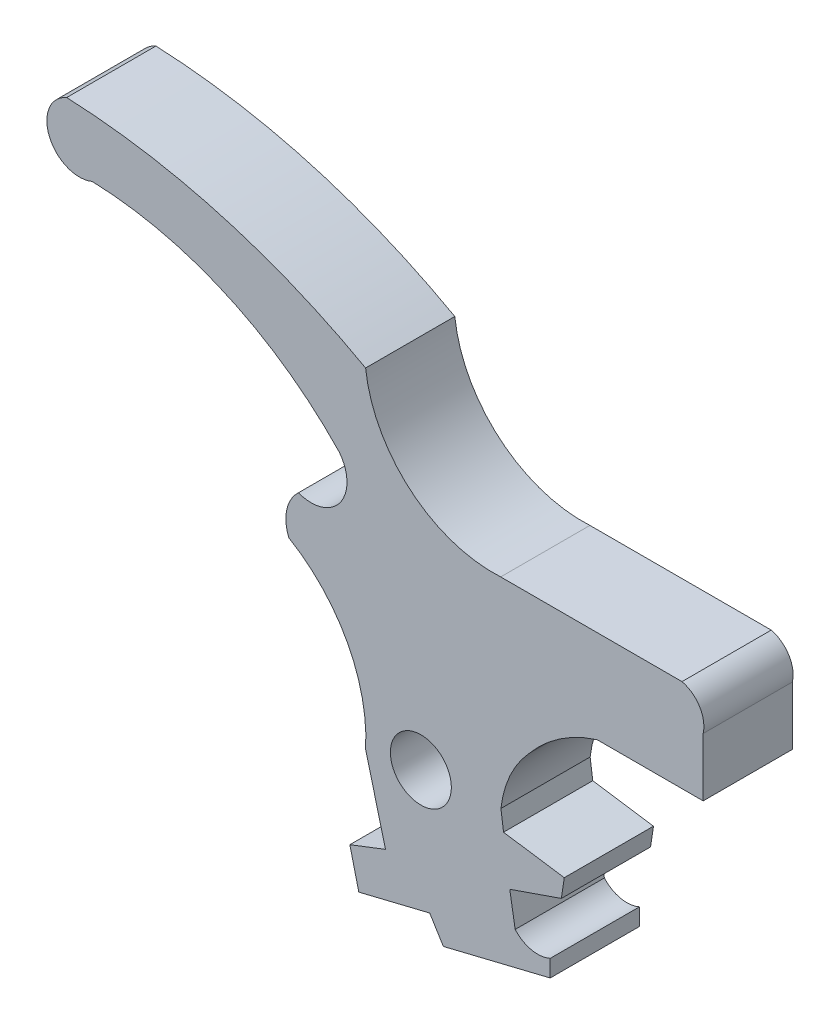
SolidWorks part; units mm, degrees
ref_plane "정면" through (0, 0, 0) normal (0, 0, 1) x (1, 0, 0)
ref_plane "윗면" through (0, 0, 0) normal (0, 1, 0) x (1, 0, 0)
ref_plane "우측면" through (0, 0, 0) normal (1, 0, 0) x (0, 0, -1)
sketch "스케치1" plane through (0, 0, 0) normal (0, 0, 1) x (1, 0, 0)
  line L0 (-3.7145, -0.6598) -> (-2.3786, -5.8179)
  line L1 (5.5588, -0.8516) -> (9.6431, -1.4566)
  line L2 (5.3688, 13.9228) -> (17.5625, 13.9228)
  line L3 (18.9842, 11.6084) -> (18.9842, 7.685)
  line L4 (18.9842, 7.685) -> (11.8569, 7.685)
  line L5 (5.3846, 0.445) -> (5.5588, -0.8516)
  line L7 (8.6994, -6.6263) -> (8.6994, -7.7709)
  line L8 (8.6994, -7.7709) -> (1.5135, -9.5269)
  line L9 (1.5135, -9.5269) -> (0.5954, -8.0402)
  line L10 (0.5954, -8.0402) -> (-4.1735, -9.2056)
  line L11 (-4.1735, -9.2056) -> (-4.775, -6.7438)
  line L12 (-4.775, -6.7438) -> (-2.3786, -5.8179)
  line L13 (9.6431, -1.4566) -> (9.4484, -2.7628)
  line L14 (9.4484, -2.7628) -> (5.9768, -3.9634)
  line L15 (5.9768, -3.9634) -> (6.3425, -6.1211)
  circle A0 centre (0, 0) radius 2.05
  arc A1 (-8.8751, 9.0777) -> (-3.7145, -0.6598) centre (-14.3053, -0.0364) cw
  arc A2 (-8.8751, 9.0777) -> (-8.2327, 12.0241) centre (-6.4445, 10.091) cw
  arc A3 (-8.2327, 12.0241) -> (-5.4873, 15.7643) centre (-7.3745, 14.2718) ccw
  arc A4 (-5.4873, 15.7643) -> (-22.1053, 23.2184) centre (-22.8782, -0.7557) ccw
  arc A5 (-22.1053, 23.2184) -> (-23.8173, 27.25) centre (-22.9613, 25.2342) cw
  arc A6 (-23.8173, 27.25) -> (-3.7176, 21.5479) centre (-25.8237, -18.099) cw
  arc A7 (-3.7176, 21.5479) -> (5.3688, 13.9228) centre (4.866, 22.55) ccw
  arc A8 (17.5625, 13.9228) -> (18.9842, 11.6084) centre (17.0971, 12.0431) cw
  arc A9 (6.3425, -6.1211) -> (8.6994, -6.6263) centre (7.8606, -4.7893) ccw
  arc A11 (11.8569, 7.685) -> (7.2905, 4.6106) centre (14.7382, -1.5228) ccw
  arc A12 (7.2905, 4.6106) -> (5.3846, 0.445) centre (12.6336, -0.3528) ccw
  dimension "D1" = 4.1
extrude "보스-돌출1" add sketch "스케치1" along normal mid plane 6
